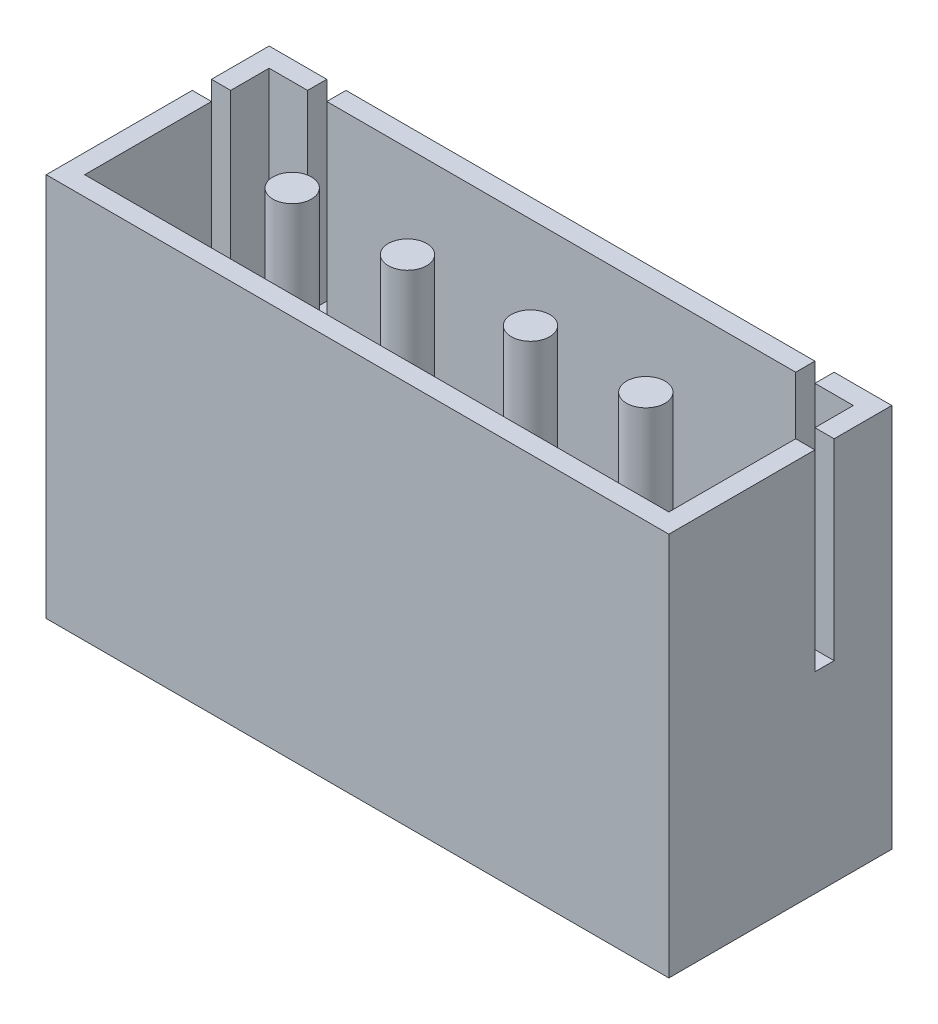
SolidWorks part; units mm, degrees
ref_plane "Спереди" through (0, 0, 0) normal (0, 0, 1) x (1, 0, 0)
ref_plane "Сверху" through (0, 0, 0) normal (0, 1, 0) x (1, 0, 0)
ref_plane "Справа" through (0, 0, 0) normal (1, 0, 0) x (0, 0, -1)
other "Configuration Table"
sketch "Эскиз1" plane through (0, 0, 0) normal (0, 1, 0) x (1, 0, 0)
  line L1 (8.1, -2.9) -> (-8.1, -2.9)
  line L2 (8.1, -2.9) -> (8.1, 2.9)
  line L3 (8.1, 2.9) -> (-8.1, 2.9)
  line L4 (-8.1, -2.9) -> (-8.1, 2.9)
  line L5 (8.1, -2.9) -> (-8.1, 2.9) construction
  line L6 (8.1, 2.9) -> (-8.1, -2.9) construction
  point P0 (0, 0)
  dimension "D1" = 16.2
  dimension "D2" = 5.8
extrude "Бобышка-Вытянуть1" add sketch "Эскиз1" along normal blind 10
sketch "Эскиз2" plane through (0, 10, 0) normal (0, 1, 0) x (1, 0, 0)
  line L0 (8.1, 2.9) -> (-8.1, 2.9) construction
  line L1 (7.6, -2.4) -> (-7.6, -2.4)
  line L2 (7.6, -2.4) -> (7.6, 2.4)
  line L3 (7.6, 2.4) -> (-7.6, 2.4)
  line L4 (-7.6, -2.4) -> (-7.6, 2.4)
  line L5 (7.6, -2.4) -> (-7.6, 2.4) construction
  line L6 (7.6, 2.4) -> (-7.6, -2.4) construction
  line L7 (-8.1, 2.9) -> (-8.1, -2.9) construction
  point P0 (0, 0)
  dimension "D1" = 0.5
  dimension "D2" = 0.5
extrude "Вырез-Вытянуть1" cut sketch "Эскиз2" against normal blind 6
sketch "Эскиз3" plane through (0, 4, 0) normal (0, 1, 0) x (1, 0, 0)
  line L0 (-7.6, 0) -> (7.6, 0) construction
  line L1 (-7.6, 2.4) -> (-7.6, -2.4) construction
  line L2 (7.6, -2.4) -> (7.6, 2.4) construction
  circle A0 centre (-4.6, 0) radius 0.5
  circle A1 centre (-1.6, 0) radius 0.5
  circle A2 centre (1.6, 0) radius 0.5
  circle A3 centre (4.6, 0) radius 0.5
  dimension "D1" = 1
  dimension "D2" = 1
  dimension "D3" = 1
  dimension "D4" = 1
  dimension "D6" = 3
  dimension "D5" = 3
  dimension "D7" = 3
  dimension "D8" = 3
extrude "Бобышка-Вытянуть2" add sketch "Эскиз3" along normal blind 6
sketch "Эскиз4" plane through (0, 10, 0) normal (0, 1, 0) x (1, 0, 0)
  line L0 (-6.6, 2.4) -> (-6.6, 2.9)
  line L1 (7.6, 2.4) -> (-7.6, 2.4) construction
  line L2 (8.1, 2.9) -> (-8.1, 2.9) construction
  line L3 (-6.1, 2.9) -> (-6.1, 2.4)
  line L4 (7.6, 2.4) -> (-7.6, 2.4) construction
  line L5 (-6.1, 2.4) -> (-6.6, 2.4)
  line L6 (-8.1, 0.9) -> (-7.6, 0.9)
  line L7 (-8.1, 2.9) -> (-8.1, -2.9) construction
  line L8 (-7.6, 2.4) -> (-7.6, -2.4) construction
  line L9 (-7.6, 0.9) -> (-7.6, 1.4)
  line L10 (-7.6, 1.4) -> (-8.1, 1.4)
  line L11 (-8.1, 1.4) -> (-8.1, 0.9)
  line L12 (-6.6, 2.9) -> (-6.1, 2.9)
  dimension "D1" = 1.5
  dimension "D2" = 1.5
  dimension "D3" = 0.5
  dimension "D4" = 0.5
extrude "Вырез-Вытянуть2" cut sketch "Эскиз4" against normal blind 5
mirror "Зеркальное отражение1" about plane through (0, 0, 0) normal (1, 0, 0) of "Вырез-Вытянуть2"
